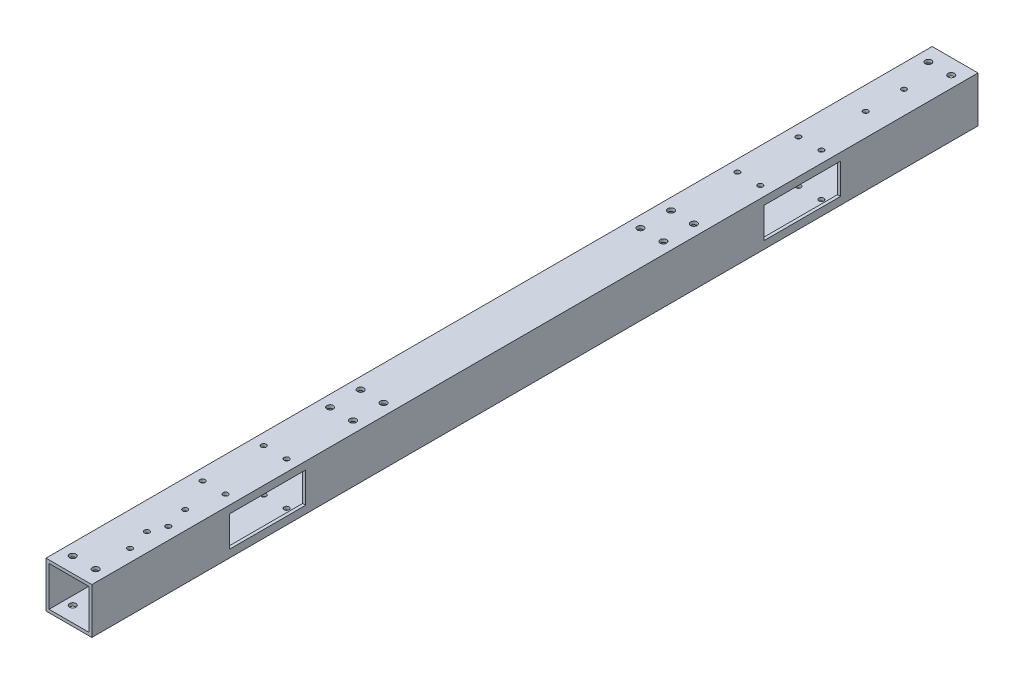
SolidWorks part; units mm, degrees
material "1060 合金"
ref_plane "前视基准面" through (0, 0, 0) normal (0, 0, 1) x (1, 0, 0)
ref_plane "上视基准面" through (0, 0, 0) normal (0, 1, 0) x (1, 0, 0)
ref_plane "右视基准面" through (0, 0, 0) normal (1, 0, 0) x (0, 0, -1)
sketch "草图1" plane through (0, 0, 0) normal (0, 0, 1) x (1, 0, 0)
  line L1 (-15, -15) -> (15, -15)
  line L2 (-15, -15) -> (-15, 15)
  line L3 (-15, 15) -> (15, 15)
  line L4 (15, -15) -> (15, 15)
  line L5 (-15, -15) -> (15, 15) construction
  line L6 (-15, 15) -> (15, -15) construction
  line L7 (-13, -13) -> (13, -13)
  line L8 (-13, -13) -> (-13, 13)
  line L9 (-13, 13) -> (13, 13)
  line L10 (13, -13) -> (13, 13)
  line L11 (-13, -13) -> (13, 13) construction
  line L12 (-13, 13) -> (13, -13) construction
  point P0 (0, 0)
  point P6 (0, 0)
  dimension "D1" = 30
  dimension "D2" = 30
  dimension "D3" = 2
extrude "凸台-拉伸1" add sketch "草图1" along normal blind 580
sketch "草图2" plane through (-15, 0, 0) normal (-1, 0, 0) x (0, 0, 1)
  line L0 (580, 15) -> (0, 15) construction
  line L1 (90, 10) -> (140, 10)
  line L2 (90, 10) -> (90, -10)
  line L3 (90, -10) -> (140, -10)
  line L4 (140, 10) -> (140, -10)
  line L5 (0, 15) -> (0, -15) construction
  line L6 (290, 138.5186) -> (290, -108.5186) construction
  line L7 (490, -10) -> (440, -10)
  line L8 (440, 10) -> (440, -10)
  line L9 (490, 10) -> (440, 10)
  line L10 (490, 10) -> (490, -10)
  point P11 (290, 15)
  dimension "D1" = 20
  dimension "D2" = 50
  dimension "D3" = 5
  dimension "D4" = 90
extrude "切除-拉伸1" cut sketch "草图2" against normal through all
sketch "草图3" plane through (0, 15, 0) normal (0, 1, 0) x (1, 0, 0)
  circle A0 centre (7.5, -10) radius 2.1
  circle A1 centre (-7.5, -10) radius 2.1
  circle A6 centre (-7.5, -570) radius 2.1
  circle A7 centre (7.5, -570) radius 2.1
extrude "切除-拉伸2" cut sketch "草图3" against normal through all
sketch "草图4" plane through (0, 15, 0) normal (0, 1, 0) x (1, 0, 0)
  line L0 (15, -580) -> (15, 0) construction
  line L1 (-15, -580) -> (-15, 0) construction
  line L2 (103.2815, -290) -> (-73.2815, -290) construction
  line L3 (85, -1217.7161) -> (85, 57.7161) construction
  circle A0 centre (7.5, -401.5675) radius 2.1
  circle A1 centre (-7.5, -401.5675) radius 2.1
  circle A2 centre (-7.5, -381.5675) radius 2.1
  circle A3 centre (7.5, -381.5675) radius 2.1
  circle A4 centre (7.5, -178.4325) radius 2.1
  circle A5 centre (-7.5, -178.4325) radius 2.1
  circle A6 centre (-7.5, -198.4325) radius 2.1
  circle A7 centre (7.5, -198.4325) radius 2.1
  circle A8 centre (162.5, -178.4325) radius 2.1
  circle A9 centre (177.5, -178.4325) radius 2.1
  circle A10 centre (177.5, -198.4325) radius 2.1
  circle A11 centre (162.5, -198.4325) radius 2.1
  circle A12 centre (162.5, -381.5675) radius 2.1
  circle A13 centre (162.5, -401.5675) radius 2.1
  circle A14 centre (177.5, -401.5675) radius 2.1
  circle A15 centre (177.5, -381.5675) radius 2.1
  point P11 (85, -580)
  point P19 (15, -290)
  dimension "D1" = 4.2
  dimension "D2" = 7.5
  dimension "D3" = 7.5
  dimension "D4" = 20
extrude "切除-拉伸3" cut sketch "草图4" against normal through all
sketch "草图7" plane through (0, 15, 0) normal (0, 1, 0) x (1, 0, 0)
  circle A0 centre (0, -33.5) radius 1.65
  circle A1 centre (0, -58.5) radius 1.65
  circle A2 centre (167, -73.0725) radius 1.65
  circle A3 centre (167, -48.0725) radius 1.65
extrude "切除-拉伸6" cut sketch "草图7" against normal through all
sketch "草图8" plane through (0, 15, 0) normal (0, 1, 0) x (1, 0, 0)
  circle A0 centre (3, -506.9275) radius 1.65
  circle A1 centre (7, -521.9757) radius 1.65
  circle A2 centre (3, -531.9275) radius 1.65
  circle A3 centre (7, -546.9757) radius 1.65
extrude "切除-拉伸7" cut sketch "草图8" against normal through all
sketch "草图9" plane through (0, 15, 0) normal (0, 1, 0) x (1, 0, 0)
  line L0 (15, -450) -> (-15, -450) construction
  line L1 (15, -580) -> (15, 0) construction
  line L3 (-15, -580) -> (-15, 0) construction
  line L4 (-15, -480) -> (15, -480) construction
  line L5 (419.4867, -290) -> (-389.4867, -290) construction
  circle A0 centre (-7.5, -445) radius 1.65
  circle A1 centre (7.5, -445) radius 1.65
  circle A2 centre (7.5, -485) radius 1.65
  circle A3 centre (-7.5, -485) radius 1.65
  circle A4 centre (-7.5, -95) radius 1.65
  circle A5 centre (7.5, -95) radius 1.65
  circle A6 centre (-7.5, -135) radius 1.65
  circle A7 centre (7.5, -135) radius 1.65
  point P20 (15, -290)
  dimension "D4" = 3.3
  dimension "D1" = 15
  dimension "D2" = 5
  dimension "D3" = 7.5
  dimension "D5" = 5
  dimension "D6" = 15
  dimension "D7" = 7.5
extrude "切除-拉伸8" cut sketch "草图9" against normal through all
